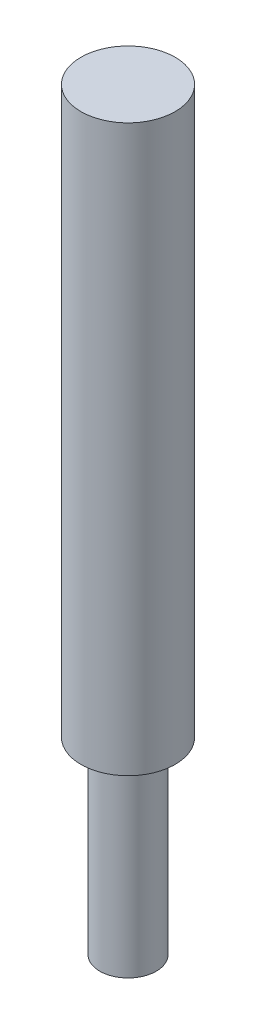
SolidWorks part; units mm, degrees
ref_plane "Front Plane" through (0, 0, 0) normal (0, 0, 1) x (1, 0, 0)
ref_plane "Top Plane" through (0, 0, 0) normal (0, 1, 0) x (1, 0, 0)
ref_plane "Right Plane" through (0, 0, 0) normal (1, 0, 0) x (0, 0, -1)
sketch "Sketch1" plane through (0, 0, 0) normal (0, 1, 0) x (1, 0, 0)
  circle A0 centre (0, 0) radius 2.5
  dimension "D1" = 5
extrude "Boss-Extrude1" add sketch "Sketch1" along normal blind 40
sketch "Sketch2" plane through (0, 0, 0) normal (0, -1, 0) x (1, 0, 0)
  circle A0 centre (0, 0) radius 2.5
  circle A1 centre (0, 0) radius 1.5
extrude "Cut-Extrude1" cut sketch "Sketch2" against normal blind 10
